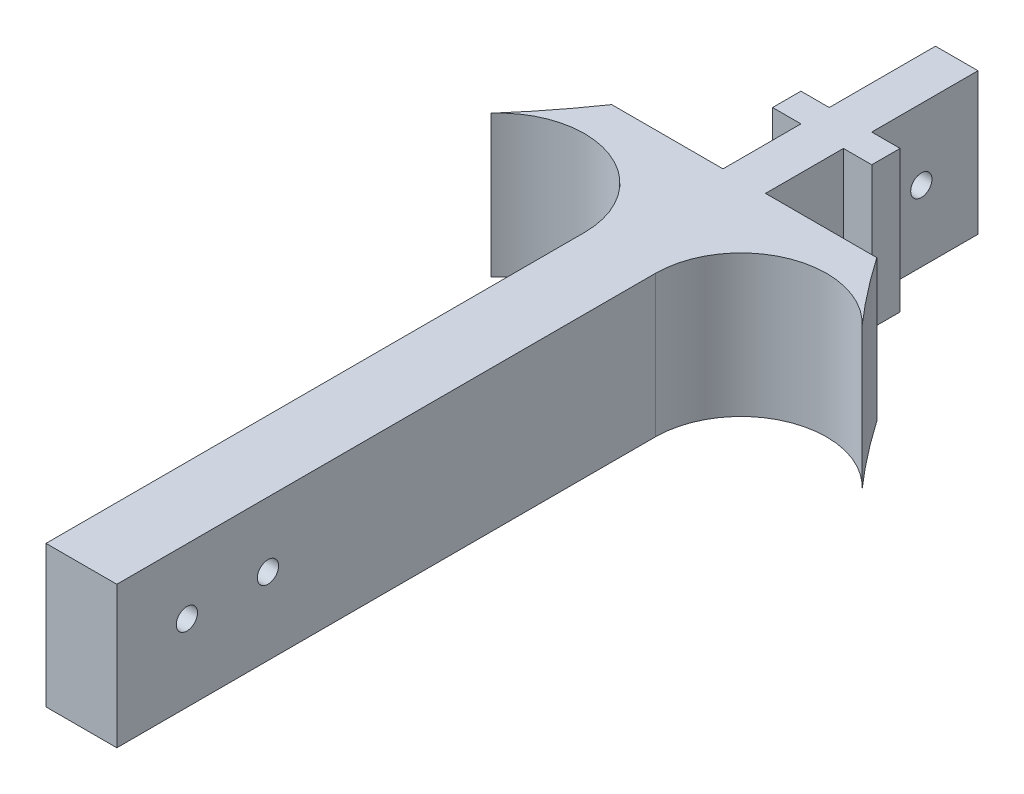
SolidWorks part; units mm, degrees
ref_plane "Plan de face" through (0, 0, 0) normal (0, 0, 1) x (1, 0, 0)
ref_plane "Plan de dessus" through (0, 0, 0) normal (0, 1, 0) x (1, 0, 0)
ref_plane "Plan de droite" through (0, 0, 0) normal (1, 0, 0) x (0, 0, -1)
sketch "Esquisse1" plane through (0, 0, 0) normal (0, 1, 0) x (1, 0, 0)
  line L0 (-3, 84.3983) -> (-3, 69.3983)
  line L1 (-3, 84.3983) -> (0, 84.3983)
  line L2 (-3, 65.3983) -> (-3, 54.3983)
  line L3 (-5, -39.1827) -> (0, -39.1827)
  line L4 (0, 84.3983) -> (0, -39.1827)
  line L5 (-3, 69.3983) -> (-7, 69.3983)
  line L6 (-3, 54.3983) -> (-18.71, 54.3983)
  line L7 (-3, 65.3983) -> (-7, 65.3983)
  line L8 (-7, 69.3983) -> (-7, 65.3983)
  line L9 (-5, 36.8425) -> (-5, -39.1827)
  arc A0 (-26.1833, 44.8157) -> (-18.71, 54.3983) centre (-105.5, 114.3795) ccw
  arc A1 (-5, 36.8425) -> (-26.1833, 44.8157) centre (-17.0922, 36.8425) ccw
  dimension "D7" = 211
  dimension "D1" = 3
  dimension "D2" = 4
  dimension "D3" = 4
  dimension "D4" = 15
  dimension "D5" = 11
  dimension "D6" = 15.71
extrude "Boss.-Extru.1" add sketch "Esquisse1" along normal blind 20
mirror "Symétrie1" about plane through (0, 20, -84.3983) normal (-1, 0, 0) of "Boss.-Extru.1"
sketch "Esquisse3" plane through (-3, 0, 0) normal (-1, 0, 0) x (0, 0, 1)
  line L2 (-84.3983, 20) -> (-69.3983, 20) construction
  line L3 (-65.3983, 20) -> (-54.3983, 20) construction
  line L4 (-84.3983, 20) -> (-84.3983, 0) construction
  circle A0 centre (-76.3983, 10) radius 1.5
  circle A1 centre (-60.3983, 10) radius 1.5
  dimension "D1" = 3
  dimension "D2" = 3
  dimension "D3" = 10
  dimension "D4" = 10
  dimension "D5" = 8
  dimension "D6" = 24
extrude "Enlèv. mat.-Extru.3" cut sketch "Esquisse3" against normal blind 20
sketch "Esquisse4" plane through (-5, 0, 0) normal (-1, 0, 0) x (0, 0, 1)
  circle A0 centre (29.292, 10.84) radius 1.5
extrude "Enlèv. mat.-Extru.4" cut sketch "Esquisse4" against normal blind 10
sketch "Esquisse5" plane through (-5, 0, 0) normal (-1, 0, 0) x (0, 0, 1)
  circle A0 centre (17.842, 10.84) radius 1.5
extrude "Enlèv. mat.-Extru.5" cut sketch "Esquisse5" against normal blind 10
